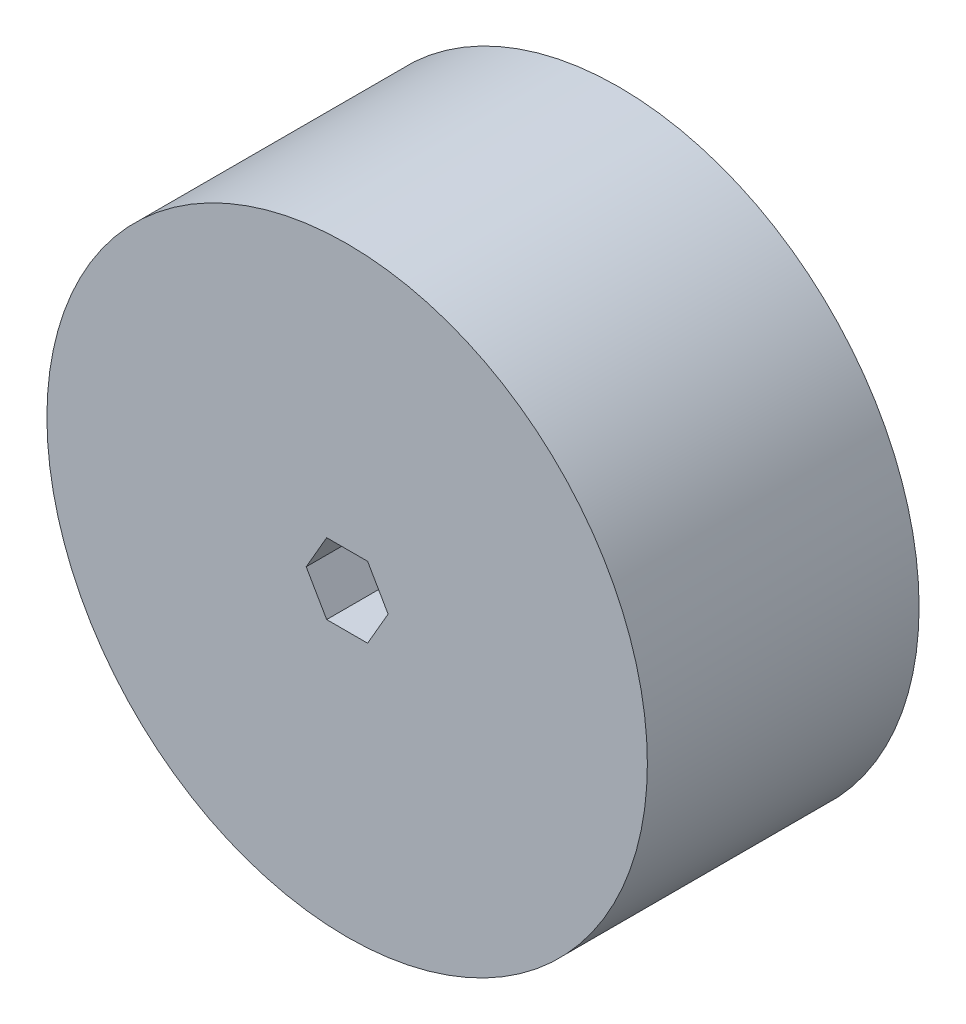
SolidWorks part; units mm, degrees
ref_plane "Front Plane" through (0, 0, 0) normal (0, 0, 1) x (1, 0, 0)
ref_plane "Top Plane" through (0, 0, 0) normal (0, 1, 0) x (1, 0, 0)
ref_plane "Right Plane" through (0, 0, 0) normal (1, 0, 0) x (0, 0, -1)
sketch "Sketch1" plane through (0, 0, 0) normal (0, 0, 1) x (1, 0, 0)
  line L0 (-3.4641, 6) -> (3.4641, 6)
  line L1 (3.4641, 6) -> (6.9282, 0)
  line L2 (6.9282, 0) -> (3.4641, -6)
  line L3 (3.4641, -6) -> (-3.4641, -6)
  line L4 (-3.4641, -6) -> (-6.9282, 0)
  line L5 (-6.9282, 0) -> (-3.4641, 6)
  line L6 (-6.9282, 0) -> (6.9282, 0) construction
  line L7 (-3.4641, 6) -> (3.4641, -6) construction
  line L8 (-3.4641, -6) -> (3.4641, 6) construction
  circle A0 centre (0, 0) radius 50.8
  circle A2 centre (0, 0) radius 6.9282
  point P5 (0, 0)
  dimension "D1" = 101.6
  dimension "D2" = 12
extrude "Boss-Extrude1" add sketch "Sketch1" along normal blind 45.974 contours A0 A2 | L4 A2 | L5 A2 | L0 A2 | L1 A2 | L2 A2 | L3 A2
sketch "Sketch2" plane through (0, 0, 0) normal (0, 0, 1) x (1, 0, 0)
  circle A0 centre (0, 0) radius 38.1
  dimension "D1" = 76.2
extrude "Cut-Extrude1" cut sketch "Sketch2" along normal blind 25.4
